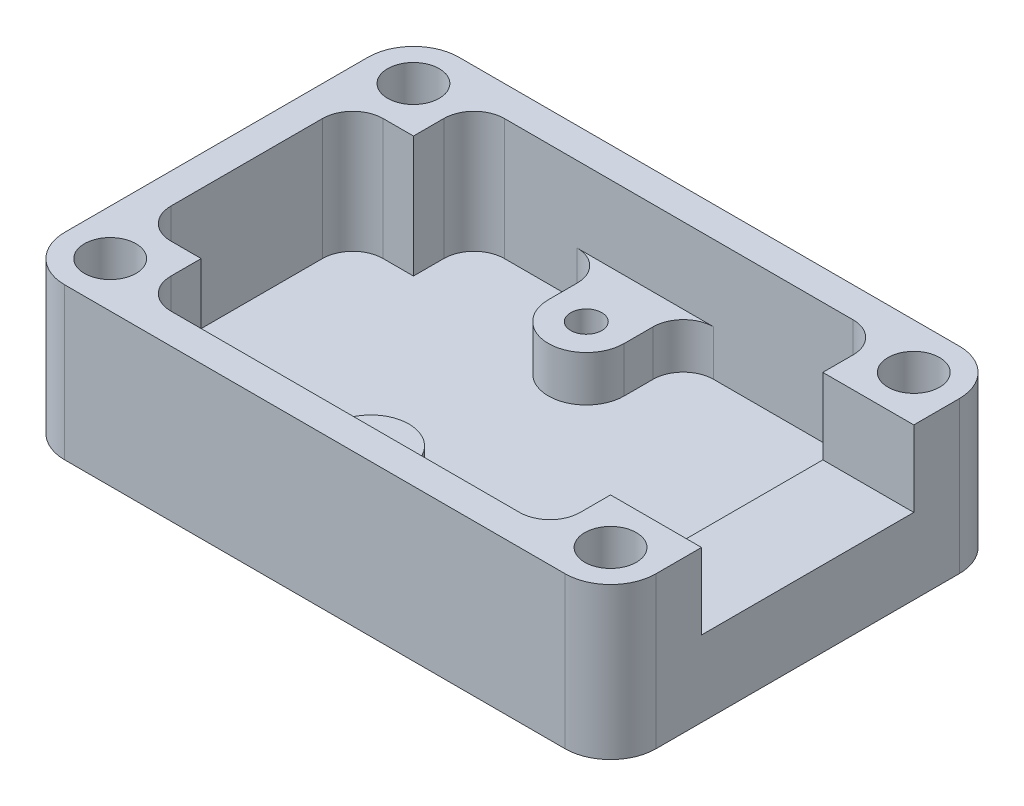
SolidWorks part; units mm, degrees
material "3.1355 (EN-AW 2024)"
ref_plane "Спереди" through (0, 0, 0) normal (0, 0, 1) x (1, 0, 0)
ref_plane "Сверху" through (0, 0, 0) normal (0, 1, 0) x (1, 0, 0)
ref_plane "Справа" through (0, 0, 0) normal (1, 0, 0) x (0, 0, -1)
sketch "Эскиз1" plane through (0, 0, 0) normal (0, 1, 0) x (1, 0, 0)
  line L1 (0, 0) -> (39, 0)
  line L2 (0, 0) -> (0, 26)
  line L3 (0, 26) -> (39, 26)
  line L4 (39, 0) -> (39, 26)
  dimension "D1" = 26
  dimension "D2" = 39
extrude "Бобышка-Вытянуть1" add sketch "Эскиз1" along normal blind 10
sketch "Эскиз2" plane through (0, 10, 0) normal (0, 1, 0) x (1, 0, 0)
  line L8 (2, 24) -> (2, 2)
  line L9 (2, 2) -> (37, 2)
  line L10 (37, 2) -> (37, 24)
  line L11 (37, 24) -> (2, 24)
  line L12 (2, 24) -> (2, 2)
  line L13 (2, 2) -> (37, 2)
  line L14 (37, 2) -> (37, 24)
  line L15 (37, 24) -> (2, 24)
  dimension "D1" = 2
extrude "Вырез-Вытянуть1" cut sketch "Эскиз2" against normal blind 8
sketch "Эскиз3" plane through (0, 2, 0) normal (0, 1, 0) x (1, 0, 0)
  line L0 (2, 13) -> (37, 13) construction
  line L1 (2, 24) -> (2, 2) construction
  line L2 (37, 2) -> (37, 24) construction
  line L3 (37, 24) -> (2, 24) construction
  line L4 (14.8, 20.1) -> (14.8, 24)
  line L5 (14.8, 24) -> (19.8, 24)
  line L6 (19.8, 24) -> (19.8, 20.1)
  line L7 (19.8, 2) -> (19.8, 5.9)
  line L8 (14.8, 2) -> (19.8, 2)
  line L9 (14.8, 5.9) -> (14.8, 2)
  arc A0 (14.8, 20.1) -> (19.8, 20.1) centre (17.3, 20.1) ccw
  arc A1 (14.8, 5.9) -> (19.8, 5.9) centre (17.3, 5.9) cw
  dimension "D3" = 2.5
  dimension "D1" = 15.3
  dimension "D2" = 3.9
extrude "Бобышка-Вытянуть2" add sketch "Эскиз3" along normal blind 3
hole_wizard "Отверстие обработанное метчиком M2.5x0.451" positions "Эскиз5" profile "Эскиз4" tap size "M2.5x0.45" standard "Ansi Metric"
sketch "Эскиз5" plane through (0, 5, 0) normal (0, 1, 0) x (1, 0, 0)
  point P0 (17.3, 20.1)
  point P3 (17.3, 5.9)
sketch "Эскиз4" plane through (17.3, 5, -20.1) normal (1, 0, 0) x (0, 0, 1)
  line L0 (0, 0) -> (0, 4.6159)
  line L1 (0, 4.6159) -> (1.025, 4)
  line L2 (1.025, 4) -> (1.025, 0)
  line L5 (1.025, 0) -> (0, 0)
  line L10 (0, 4.6159) -> (-1.025, 4) construction
  line L11 (0, -6.35) -> (0, 107.95) construction
  dimension "Диаметр сверла" = 2.05
  dimension "Глубина сверла" = 4
  dimension "Угол заточки сверла" = 118
cosmetic thread "Отверстие резьбы1" parameters "D1"=3, "D2"=2.5
cosmetic thread "Отверстие резьбы2" parameters "D1"=3, "D2"=2.5
sketch "Эскиз6" plane through (0, 2, 0) normal (0, 1, 0) x (1, 0, 0)
  line L0 (33, 20) -> (39, 26) construction
  line L2 (19.5, 26) -> (19.5, 13) construction
  line L3 (6, 0) -> (6, 6)
  line L5 (0, 0) -> (6, 0)
  line L6 (0, 6) -> (0, 0)
  line L7 (33, 26) -> (33, 20)
  line L8 (39, 26) -> (0, 26) construction
  line L9 (33, 20) -> (39, 20)
  line L10 (39, 0) -> (39, 26) construction
  line L11 (39, 20) -> (39, 26)
  line L12 (39, 26) -> (33, 26)
  line L13 (39, 0) -> (33, 0)
  line L14 (39, 6) -> (39, 0)
  line L15 (33, 6) -> (39, 6)
  line L16 (33, 0) -> (33, 6)
  line L17 (5, 13) -> (0, 13) construction
  line L18 (0, 26) -> (0, 0) construction
  line L19 (6, 6) -> (0, 6)
  line L20 (6, 26) -> (6, 20)
  line L21 (6, 20) -> (0, 20)
  line L22 (0, 20) -> (0, 26)
  line L23 (0, 26) -> (6, 26)
  point P0 (36, 3)
  point P4 (3, 3)
  point P9 (3, 23)
  point P22 (36, 23)
  dimension "D3" = 6
  dimension "D4" = 6
extrude "Бобышка-Вытянуть3" add sketch "Эскиз6" along normal through all
hole_wizard "Отверстие с зазором M32" positions "Эскиз13" profile "Эскиз12" hole size "M3" standard "Ansi Metric" end condition through all
sketch "Эскиз13" plane through (0, 10, 0) normal (0, 1, 0) x (1, 0, 0)
  point P0 (3, 23)
  point P3 (36, 23)
  point P6 (36, 3)
  point P9 (3, 3)
sketch "Эскиз12" plane through (3, 10, -23) normal (1, 0, 0) x (0, 0, 1)
  line L0 (0, 0) -> (0, 10)
  line L1 (0, 10) -> (1.7, 10)
  line L2 (1.7, 10) -> (1.7, 0)
  line L5 (1.7, 0) -> (0, 0)
  line L11 (0, -6.35) -> (0, 107.95) construction
  dimension "Диаметр сквозного отверстия" = 3.4
  dimension "Глубина сквозного отверстия" = 10
sketch "Эскиз14" plane through (39, 0, 0) normal (1, 0, 0) x (0, 0, -1)
  line L0 (6, 10) -> (20, 10)
  line L1 (0, 10) -> (26, 10) construction
  line L4 (6, 10) -> (6, 5)
  line L6 (6, 5) -> (20, 5)
  line L7 (23, 5) -> (3, 5) construction
  line L8 (20, 5) -> (20, 10)
  point P4 (13, 10)
  dimension "D1" = 14
  dimension "D2" = 5
extrude "Вырез-Вытянуть2" cut sketch "Эскиз14" against normal up to next
sketch "Эскиз15" plane through (37, 0, 0) normal (-1, 0, 0) x (0, 0, 1)
  line L4 (-6, 2) -> (-6, 5)
  line L5 (-6, 5) -> (-20, 5)
  line L6 (-20, 5) -> (-20, 2)
  line L7 (-20, 2) -> (-6, 2)
  line L8 (-6, 2) -> (-6, 5)
  line L9 (-6, 5) -> (-20, 5)
  line L10 (-20, 5) -> (-20, 2)
  line L11 (-20, 2) -> (-6, 2)
  dimension "D1" = 0
extrude "Бобышка-Вытянуть4" add sketch "Эскиз15" along normal up to surface (4 mm away) up to face at (33, 6, -4)
fillet "Скругление1" radius 2 10 edges at (2, 6, -6) (6, 6, -2) (14.8, 3.5, -2) (19.8, 3.5, -2) (33, 6, -2) (33, 6, -24) (19.8, 3.5, -24) (14.8, 3.5, -24) (6, 6, -24) (2, 6, -20)
fillet "Скругление2" radius 3 4 edges at (0, 5, 0) (39, 5, 0) (39, 5, -26) (0, 5, -26)
